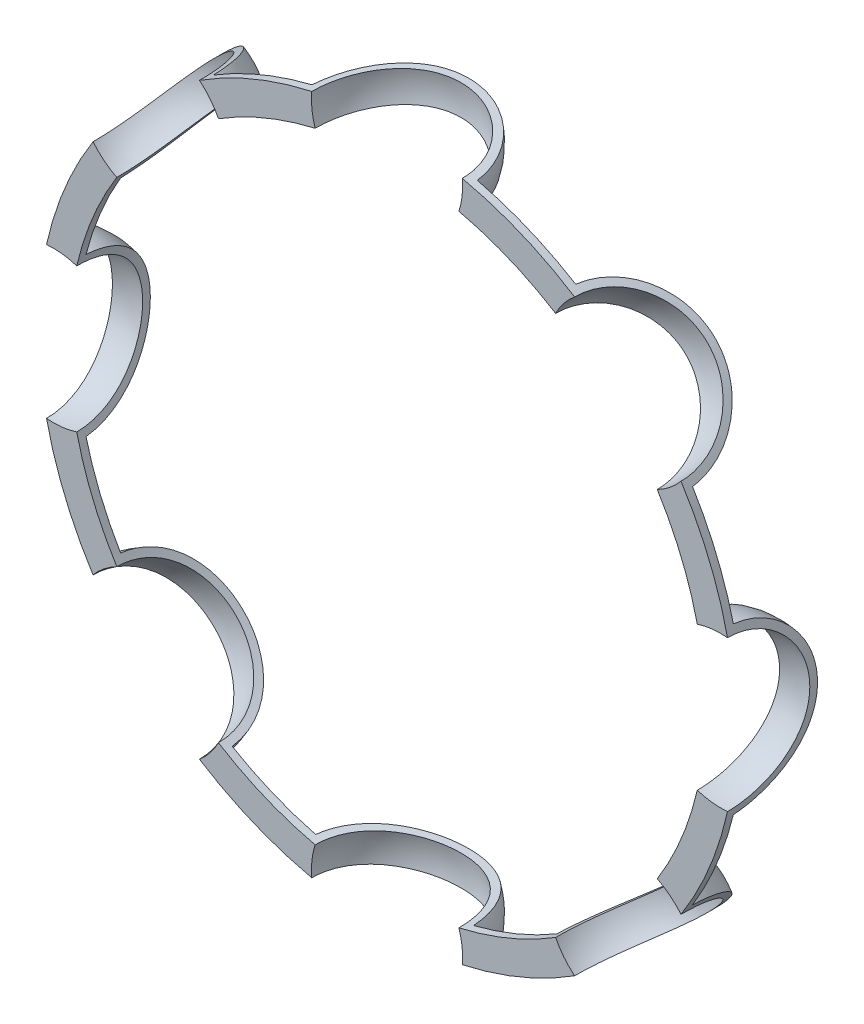
SolidWorks part; units mm, degrees
ref_plane "Front Plane" through (0, 0, 0) normal (0, 0, 1) x (1, 0, 0)
ref_plane "Top Plane" through (0, 0, 0) normal (0, 1, 0) x (1, 0, 0)
ref_plane "Right Plane" through (0, 0, 0) normal (1, 0, 0) x (0, 0, -1)
sketch "Sketch1" plane through (0, 0, 0) normal (0, 0, 1) x (1, 0, 0)
  line L0 (0, 0) -> (1407.9924, 583.2096)
  line L2 (0, 0) -> (1407.9924, -583.2096)
  arc A0 (1407.9924, -583.2096) -> (1407.9924, 583.2096) centre (0, 0) ccw
extrude "Boss-Extrude1" add sketch "Sketch1" along normal blind 25.4 contours A0 L0 L2
sketch "Sketch4" plane through (0, 0, 0) normal (0, 1, 0) x (1, 0, 0)
  line L0 (0, 0) -> (1121.156, 0) construction
  line L1 (0, 0) -> (1407.9924, 0) construction
  line L2 (1121.156, -25.4) -> (1121.156, 254)
  line L3 (0, -25.4) -> (1407.9924, -25.4) construction
  line L4 (1121.156, -25.4) -> (1400.556, -25.4)
  arc A0 (1400.556, -25.4) -> (1121.156, 254) centre (1121.156, -25.4) ccw
revolve "Revolve5" add sketch "Sketch4" angle 360 about L2
sketch "Sketch6" plane through (0, 0, 0) normal (0, 1, 0) x (1, 0, 0)
  line L0 (1121.156, -25.4) -> (1375.1516, -25.4)
  line L1 (0, -25.4) -> (1407.9924, -25.4) construction
  line L2 (1121.156, -25.4) -> (1121.156, 228.6)
  arc A0 (1375.1516, -25.4) -> (1121.156, 228.5956) centre (1121.156, -25.4) ccw
revolve "Cut-Revolve1" cut sketch "Sketch6" angle 360 about L2
mirror "Mirror1" about plane through (0, 0, 25.4) normal (-0.3827, 0.9239, 0) of bodies 105
mirror "Mirror2" about plane through (0, 0, 25.4) normal (0.9239, -0.3827, 0) of bodies 106
mirror "Mirror3" about plane through (0, 0, 25.4) normal (0.3827, 0.9239, 0) of bodies 107
sketch "Sketch7" plane through (0, 0, 0) normal (0, 0, 1) x (1, 0, 0)
  line L1 (-1779.5253, 1747.6912) -> (1779.5253, 1747.6912)
  line L2 (-1779.5253, 1747.6912) -> (-1779.5253, -1747.6912)
  line L3 (-1779.5253, -1747.6912) -> (1779.5253, -1747.6912)
  line L4 (1779.5253, 1747.6912) -> (1779.5253, -1747.6912)
  line L5 (-1779.5253, 1747.6912) -> (1779.5253, -1747.6912) construction
  line L6 (-1779.5253, -1747.6912) -> (1779.5253, 1747.6912) construction
  circle A0 centre (0, 0) radius 1070.356
  circle A1 centre (0, 0) radius 1171.956
extrude "Cut-Extrude2" cut sketch "Sketch7" against normal through all both and the other way through all contours A0 | L4 L1 L2 L3 A1
